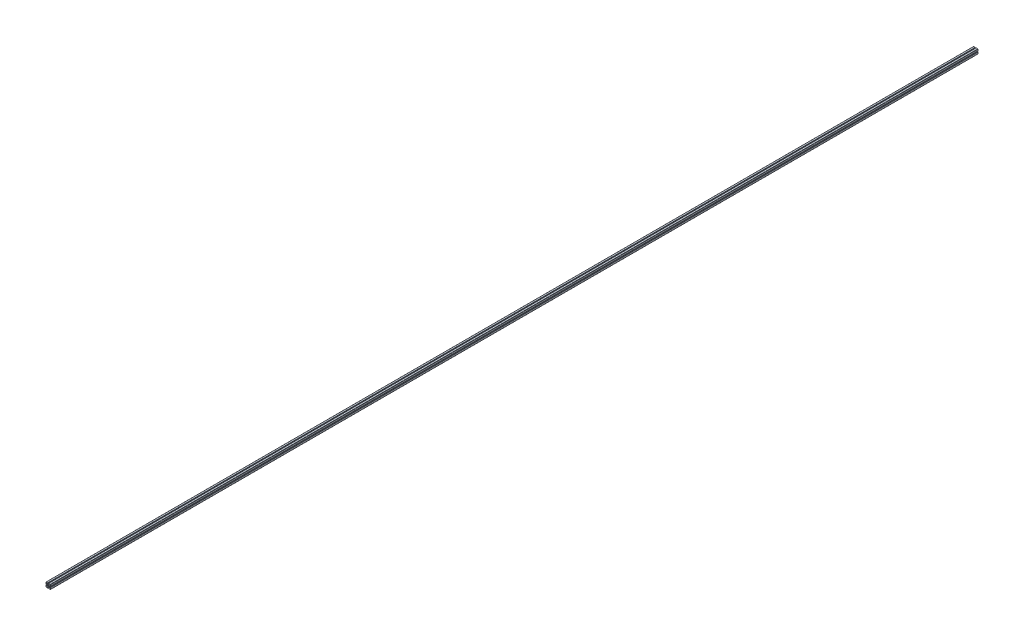
SolidWorks part; units mm, degrees
ref_plane "Front" through (0, 0, 0) normal (0, 0, 1) x (1, 0, 0)
ref_plane "Top" through (0, 0, 0) normal (0, 1, 0) x (1, 0, 0)
ref_plane "Right" through (0, 0, 0) normal (1, 0, 0) x (0, 0, -1)
sketch "草图1" plane through (0, 0, 0) normal (0, 0, 1) x (1, 0, 0)
  line L1 (-20, 20) -> (20, 20)
  line L2 (-20, 20) -> (-20, -20)
  line L3 (-20, -20) -> (20, -20)
  line L4 (20, 20) -> (20, -20)
  line L5 (-20, 20) -> (20, -20) construction
  line L6 (-20, -20) -> (20, 20) construction
  point P0 (0, 0)
  dimension "D1" = 40
extrude "凸台-拉伸1" add sketch "草图1" along normal blind 1223 and the other way blind 7111
sketch "草图2" plane through (0, 0, 1223) normal (0, 0, 1) x (1, 0, 0)
  circle A0 centre (0, 0) radius 4.05
  dimension "D1" = 8.1
extrude "切除-拉伸1" cut sketch "草图2" against normal blind 10000
sketch "草图4" plane through (0, 0, 1223) normal (0, 0, 1) x (1, 0, 0)
  line L0 (20, -20) -> (20, 20) construction
  line L1 (20, 0) -> (20, 4)
  line L2 (20, 0) -> (20, -2.652)
  line L3 (7.8769, 2.6) -> (7.8769, -2.6)
  line L4 (20, 4) -> (16, 4)
  line L5 (20, -2.652) -> (16, -2.652)
  line L6 (16, 10.5) -> (16, 4)
  line L7 (16, 10.5) -> (7.8769, 2.6)
  line L8 (16, -10.5) -> (7.8769, -2.6)
  line L9 (16, -2.652) -> (16, -10.5)
  point P11 (7.8769, 0)
  point P12 (16, 0)
extrude "切除-拉伸2" cut sketch "草图4" against normal blind 10000
fillet "圆角1" radius 1 8 edges at (16, 10.5, -2944) (16, -10.5, -2944) (7.8769, 2.6, -2944) (20, -2.652, -2944) (16, -2.652, -2944) (20, 4, -2944) (16, 4, -2944) (7.8769, -2.6, -2944)
pattern_circular "阵列(圆周)2" count 4 over 360 about axis through (0, 0, 0) along (0, 0, 1) of "切除-拉伸2"
fillet "圆角2" radius 1 8 edges at (10.5, 16, -2944) (-10.5, 16, -2944) (-4, 20, -2944) (2.652, 16, -2944) (2.652, 20, -2944) (-2.6, 7.8769, -2944) (-4, 16, -2944) (2.6, 7.8769, -2944)
fillet "圆角3" radius 1 8 edges at (-7.8769, -2.6, -2944) (-7.8769, 2.6, -2944) (-20, 2.652, -2944) (-16, 10.5, -2944) (-20, -4, -2944) (-16, -4, -2944) (-16, -10.5, -2944) (-16, 2.652, -2944)
fillet "圆角4" radius 1 8 edges at (4, -20, -2944) (4, -16, -2944) (10.5, -16, -2944) (-2.652, -20, -2944) (2.6, -7.8769, -2944) (-2.6, -7.8769, -2944) (-2.652, -16, -2944) (-10.5, -16, -2944)
fillet "圆角5" radius 2 4 edges at (-20, -20, -2944) (20, -20, -2944) (-20, 20, -2944) (20, 20, -2944)
